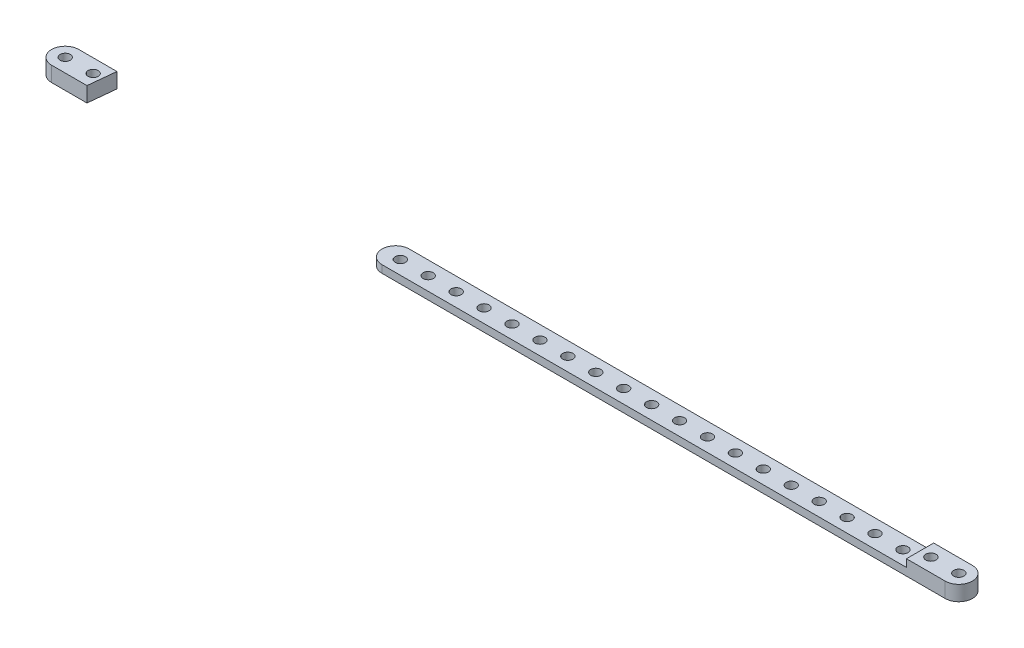
SolidWorks part; units mm, degrees
ref_plane "Front Plane" through (0, 0, 0) normal (0, 0, 1) x (1, 0, 0)
ref_plane "Top Plane" through (0, 0, 0) normal (0, 1, 0) x (1, 0, 0)
ref_plane "Right Plane" through (0, 0, 0) normal (1, 0, 0) x (0, 0, -1)
ref_plane "Plane1" through (0, 6.35, 0) normal (0, 1, 0) x (1, 0, 0)
sketch "Sketch1" plane through (0, 6.35, 0) normal (0, 1, 0) x (1, 0, 0)
  line L0 (187.7568, 5.715) -> (-187.7568, 5.715)
  line L1 (-187.7568, -5.715) -> (187.7568, -5.715)
  arc A0 (187.7568, -5.715) -> (187.7568, 5.715) centre (187.7568, 0) ccw
  arc A1 (-187.7568, 5.715) -> (-187.7568, -5.715) centre (-187.7568, 0) ccw
  circle A2 centre (187.7568, 0) radius 2.1336
  circle A3 centre (176.022, 0) radius 2.1336
  circle A4 centre (164.2872, 0) radius 2.1336
  circle A5 centre (152.5524, 0) radius 2.1336
  circle A6 centre (140.8176, 0) radius 2.1336
  circle A7 centre (129.0828, 0) radius 2.1336
  circle A8 centre (117.348, 0) radius 2.1336
  circle A9 centre (105.6132, 0) radius 2.1336
  circle A10 centre (93.8784, 0) radius 2.1336
  circle A11 centre (82.1436, 0) radius 2.1336
  circle A12 centre (70.4088, 0) radius 2.1336
  circle A13 centre (58.674, 0) radius 2.1336
  circle A14 centre (46.9392, 0) radius 2.1336
  circle A15 centre (35.2044, 0) radius 2.1336
  circle A16 centre (23.4696, 0) radius 2.1336
  circle A17 centre (11.7348, 0) radius 2.1336
  circle A18 centre (0, 0) radius 2.1336
  circle A19 centre (-11.7348, 0) radius 2.1336
  circle A20 centre (-23.4696, 0) radius 2.1336
  circle A21 centre (-35.2044, 0) radius 2.1336
  circle A22 centre (-46.9392, 0) radius 2.1336
  circle A23 centre (-58.674, 0) radius 2.1336
  circle A24 centre (-70.4088, 0) radius 2.1336
  circle A25 centre (-82.1436, 0) radius 2.1336
  circle A26 centre (-93.8784, 0) radius 2.1336
  circle A27 centre (-105.6132, 0) radius 2.1336
  circle A28 centre (-117.348, 0) radius 2.1336
  circle A29 centre (-129.0828, 0) radius 2.1336
  circle A30 centre (-140.8176, 0) radius 2.1336
  circle A31 centre (-152.5524, 0) radius 2.1336
  circle A32 centre (-164.2872, 0) radius 2.1336
  circle A33 centre (-176.022, 0) radius 2.1336
  circle A34 centre (-187.7568, 0) radius 2.1336
  dimension "D1" = 11.43
extrude "Boss-Extrude1" add sketch "Sketch1" against normal blind 6.35
sketch "Sketch2" plane through (0, 6.35, 0) normal (0, 1, 0) x (1, 0, 0)
  line L0 (-187.7568, -5.715) -> (187.7568, -5.715) construction
  line L1 (187.7568, 5.715) -> (-187.7568, 5.715) construction
  line L2 (-117.348, -5.715) -> (-172.9896, -6.5933)
  line L3 (-172.9896, -6.5933) -> (-171.1504, 11.2737)
  line L4 (-171.1504, 11.2737) -> (-117.348, 5.715)
  arc A0 (-117.348, -5.715) -> (-117.348, 5.715) centre (-117.348, 0) cw
extrude "Cut-Extrude1" cut sketch "Sketch2" against normal through all
sketch "Sketch3" plane through (0, 6.35, 0) normal (0, 1, 0) x (1, 0, 0)
  line L1 (-134.3808, -55.3218) -> (171.4713, -55.3218)
  line L2 (-134.3808, -55.3218) -> (-134.3808, 57.6005)
  line L3 (-134.3808, 57.6005) -> (171.4713, 57.6005)
  line L4 (171.4713, -55.3218) -> (171.4713, 57.6005)
extrude "Cut-Extrude2" cut sketch "Sketch3" against normal blind 3.175
sketch "Sketch5" plane through (0, 3.175, 0) normal (0, 1, 0) x (1, 0, 0)
  line L0 (-117.348, -5.715) -> (171.4713, -5.715) construction
  line L1 (171.4713, 5.715) -> (-117.348, 5.715) construction
  line L2 (-48.895, -5.715) -> (-130.8362, -54.309)
  line L3 (-130.8362, -54.309) -> (-122.9873, 82.9193)
  line L4 (-122.9873, 82.9193) -> (-48.895, 5.715)
  arc A0 (-48.895, -5.715) -> (-48.895, 5.715) centre (-48.895, 0) cw
extrude "Cut-Extrude3" cut sketch "Sketch5" against normal through all
